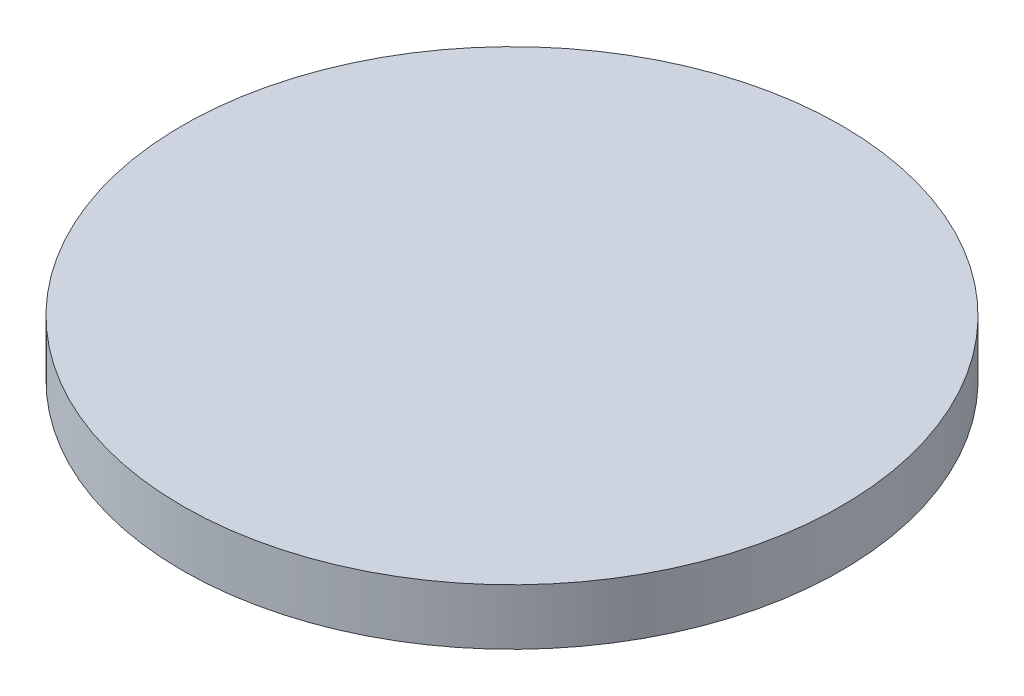
SolidWorks part; units mm, degrees
ref_plane "Front Plane" through (0, 0, 0) normal (0, 0, 1) x (1, 0, 0)
ref_plane "Top Plane" through (0, 0, 0) normal (0, 1, 0) x (1, 0, 0)
ref_plane "Right Plane" through (0, 0, 0) normal (1, 0, 0) x (0, 0, -1)
sketch "Sketch1" plane through (0, 0, 0) normal (0, 1, 0) x (1, 0, 0)
  circle A0 centre (0, 0) radius 16.75
  dimension "D1" = 33.5
extrude "Boss-Extrude1" add sketch "Sketch1" along normal blind 2.84
